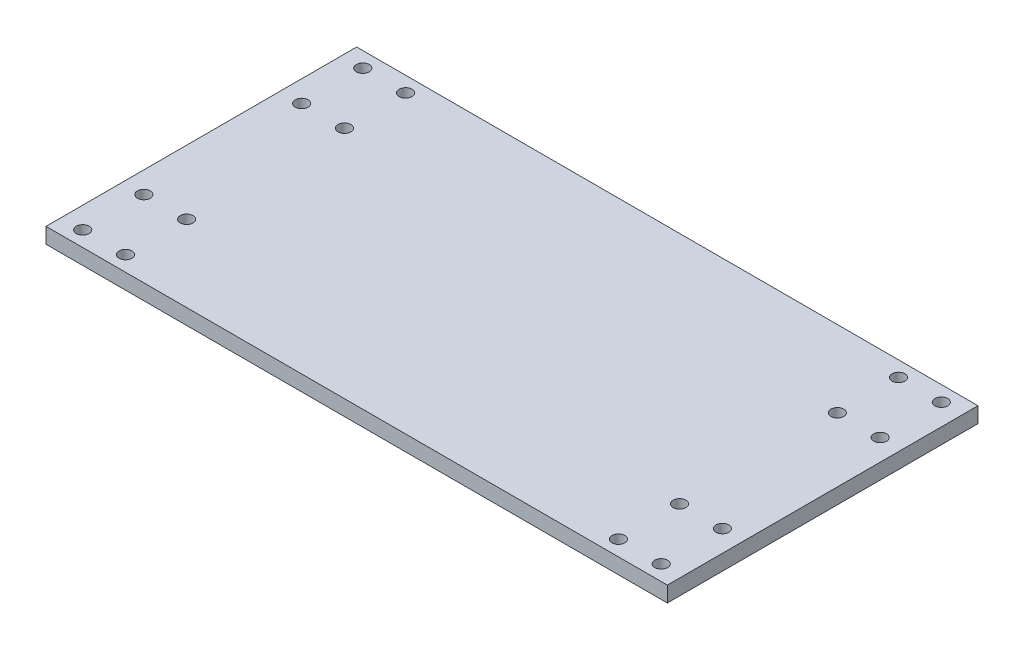
SolidWorks part; units mm, degrees
ref_plane "Front Plane" through (0, 0, 0) normal (0, 0, 1) x (1, 0, 0)
ref_plane "Top Plane" through (0, 0, 0) normal (0, 1, 0) x (1, 0, 0)
ref_plane "Right Plane" through (0, 0, 0) normal (1, 0, 0) x (0, 0, -1)
sketch "Sketch1" plane through (0, 0, 0) normal (0, 1, 0) x (1, 0, 0)
  line L1 (0, 0) -> (203.2, 0)
  line L2 (0, 0) -> (0, -101.6)
  line L3 (0, -101.6) -> (203.2, -101.6)
  line L4 (203.2, 0) -> (203.2, -101.6)
  dimension "D1" = 203.2
  dimension "D2" = 101.6
extrude "Boss-Extrude1" add sketch "Sketch1" along normal blind 5.08
hole_wizard "Tap Drill for M5x0.8 Tap1" positions "Sketch4" profile "Sketch5" hole size "M5x0.8" standard "ANSI Metric" end condition through all
sketch "Sketch4" plane through (0, 0, 0) normal (0, -1, 0) x (-1, 0, 0)
  circle A0 centre (-196.2, -5) radius 2.1 construction
  circle A1 centre (-182.2, -5) radius 2.1 construction
  circle A2 centre (-196.2, -25) radius 2.1 construction
  circle A3 centre (-182.2, -25) radius 2.1 construction
  circle A4 centre (-196.2, -76.6) radius 2.1 construction
  point P0 (-196.2, -5)
  point P2 (-182.2, -5)
  point P4 (-196.2, -25)
  point P6 (-182.2, -25)
  point P8 (-21, -5)
  point P10 (-7, -5)
  point P12 (-21, -25)
  point P14 (-7, -25)
  point P16 (-7, -76.6)
  point P18 (-196.2, -76.6)
  point P20 (-182.2, -76.6)
  point P22 (-182.2, -96.6)
  point P24 (-196.2, -96.6)
  point P26 (-21, -76.6)
  point P28 (-21, -96.6)
  point P30 (-7, -96.6)
  point P34 (0, 0)
  point P37 (0, 0)
  point P38 (0, 0)
  point P39 (0, 0)
  point P42 (0, 0)
  point P45 (0, 0)
  point P48 (0, 0)
  point P49 (0, 0)
  point P52 (-180.7, -76.6)
  point P54 (-180.7, -96.6)
  point P56 (-195.7, -96.6)
  point P58 (-22.5, -5)
  point P60 (-7.5, -5)
  point P62 (-22.5, -25)
  point P64 (-7.5, -25)
  point P66 (-7.5, -76.6)
  point P68 (-22.5, -76.6)
  point P70 (-22.5, -96.6)
  point P72 (-7.5, -96.6)
sketch "Sketch5" plane through (196.2, 0, 5) normal (1, 0, 0) x (0, 0, -1)
  line L0 (0, 0) -> (0, 5.08)
  line L1 (0, 5.08) -> (2.1, 5.08)
  line L2 (2.1, 5.08) -> (2.1, 0)
  line L5 (2.1, 0) -> (0, 0)
  line L11 (0, -6.35) -> (0, 107.95) construction
  dimension "Thru Hole Dia." = 4.2
  dimension "Thru Hole Depth" = 5.08
